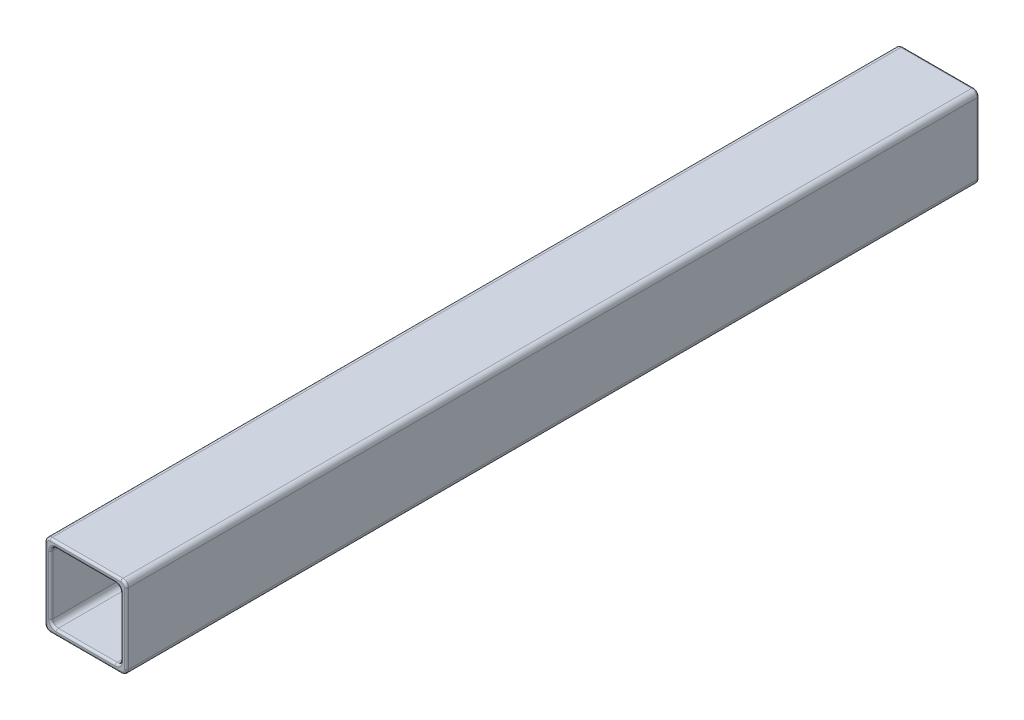
SolidWorks part; units mm, degrees
material "ASTM A500 Grade B Steel"
ref_plane "Front Plane" through (0, 0, 0) normal (0, 0, 1) x (1, 0, 0)
ref_plane "Top Plane" through (0, 0, 0) normal (0, 1, 0) x (1, 0, 0)
ref_plane "Right Plane" through (0, 0, 0) normal (1, 0, 0) x (0, 0, -1)
sketch "Sketch1" plane through (0, 0, 0) normal (0, 0, 1) x (1, 0, 0)
  line L0 (5.3086, -2.7686) -> (32.7914, -2.7686)
  line L1 (2.54, 0) -> (35.56, 0)
  line L2 (0, -2.54) -> (0, -35.56)
  line L3 (2.54, -38.1) -> (35.56, -38.1)
  line L4 (38.1, -2.54) -> (38.1, -35.56)
  line L5 (35.3314, -5.3086) -> (35.3314, -32.7914)
  line L6 (5.3086, -35.3314) -> (32.7914, -35.3314)
  line L7 (2.7686, -5.3086) -> (2.7686, -32.7914)
  line L8 (0, 0) -> (0, -38.1) construction
  line L9 (0, -38.1) -> (38.1, -38.1) construction
  line L10 (38.1, 0) -> (38.1, -38.1) construction
  line L11 (2.7686, -2.7686) -> (2.7686, -35.3314) construction
  line L12 (2.7686, -35.3314) -> (35.3314, -35.3314) construction
  line L13 (35.3314, -2.7686) -> (35.3314, -35.3314) construction
  line L14 (2.7686, -2.7686) -> (35.3314, -2.7686) construction
  line L15 (0, 0) -> (38.1, 0) construction
  arc A0 (0, -35.56) -> (2.54, -38.1) centre (2.54, -35.56) ccw
  arc A1 (38.1, -35.56) -> (35.56, -38.1) centre (35.56, -35.56) cw
  arc A2 (2.7686, -32.7914) -> (5.3086, -35.3314) centre (5.3086, -32.7914) ccw
  arc A3 (32.7914, -35.3314) -> (35.3314, -32.7914) centre (32.7914, -32.7914) ccw
  arc A4 (35.3314, -5.3086) -> (32.7914, -2.7686) centre (32.7914, -5.3086) ccw
  arc A5 (38.1, -2.54) -> (35.56, 0) centre (35.56, -2.54) ccw
  arc A6 (0, -2.54) -> (2.54, 0) centre (2.54, -2.54) cw
  arc A7 (5.3086, -2.7686) -> (2.7686, -5.3086) centre (5.3086, -5.3086) ccw
  point P12 (0, -38.1)
  dimension "D4" = 2.54
  dimension "D3" = 2.7686
extrude "Boss-Extrude1" add sketch "Sketch1" along normal blind 397
sketch "Sketch2" plane through (0, 0, 0) normal (0, 0, -1) x (-1, 0, 0)
  line L0 (-32.7914, -2.7686) -> (-5.3086, -2.7686) construction
  line L1 (-32.7914, -2.7686) -> (-5.3086, -2.7686)
  line L2 (-2.7686, -5.3086) -> (-2.7686, -32.7914) construction
  line L3 (-2.7686, -5.3086) -> (-2.7686, -32.7914)
  line L4 (0, -35.56) -> (0, -2.54)
  line L5 (-2.54, 0) -> (-35.56, 0)
  line L6 (-38.1, -2.54) -> (-38.1, -35.56)
  line L7 (-35.56, -38.1) -> (-2.54, -38.1)
  line L8 (0, -35.56) -> (0, -2.54)
  line L9 (-2.54, 0) -> (-35.56, 0)
  line L10 (-38.1, -2.54) -> (-38.1, -35.56)
  line L11 (-35.56, -38.1) -> (-2.54, -38.1)
  line L12 (-35.3314, -32.7914) -> (-35.3314, -5.3086) construction
  line L13 (-5.3086, -35.3314) -> (-32.7914, -35.3314) construction
  line L14 (-35.3314, -32.7914) -> (-35.3314, -5.3086)
  line L15 (-5.3086, -35.3314) -> (-32.7914, -35.3314)
  arc A0 (-2.7686, -5.3086) -> (-5.3086, -2.7686) centre (-5.3086, -5.3086) ccw construction
  arc A1 (-2.7686, -5.3086) -> (-5.3086, -2.7686) centre (-5.3086, -5.3086) ccw
  arc A2 (-32.7914, -2.7686) -> (-35.3314, -5.3086) centre (-32.7914, -5.3086) ccw construction
  arc A3 (-35.3314, -32.7914) -> (-32.7914, -35.3314) centre (-32.7914, -32.7914) ccw construction
  arc A4 (-2.54, -38.1) -> (0, -35.56) centre (-2.54, -35.56) ccw
  arc A5 (0, -2.54) -> (-2.54, 0) centre (-2.54, -2.54) ccw
  arc A6 (-35.56, 0) -> (-38.1, -2.54) centre (-35.56, -2.54) ccw
  arc A7 (-38.1, -35.56) -> (-35.56, -38.1) centre (-35.56, -35.56) ccw
  arc A8 (-2.54, -38.1) -> (0, -35.56) centre (-2.54, -35.56) ccw
  arc A9 (0, -2.54) -> (-2.54, 0) centre (-2.54, -2.54) ccw
  arc A10 (-35.56, 0) -> (-38.1, -2.54) centre (-35.56, -2.54) ccw
  arc A11 (-38.1, -35.56) -> (-35.56, -38.1) centre (-35.56, -35.56) ccw
  arc A12 (-5.3086, -35.3314) -> (-2.7686, -32.7914) centre (-5.3086, -32.7914) ccw construction
  arc A13 (-32.7914, -2.7686) -> (-35.3314, -5.3086) centre (-32.7914, -5.3086) ccw
  arc A14 (-35.3314, -32.7914) -> (-32.7914, -35.3314) centre (-32.7914, -32.7914) ccw
  arc A15 (-5.3086, -35.3314) -> (-2.7686, -32.7914) centre (-5.3086, -32.7914) ccw
  dimension "D1" = 0
extrude "Boss-Extrude2" add sketch "Sketch2" along normal up to surface (0.6787 mm away)
fillet "Fillet1" radius 1 32 edges at (37.3561, -37.3561, -0.6787) (38.1, -19.05, -0.6787) (37.3561, -0.7439, -0.6787) (19.05, 0, -0.6787) (0.7439, -0.7439, -0.6787) (0, -19.05, -0.6787) (0.7439, -37.3561, -0.6787) (19.05, -38.1, -0.6787) (35.3314, -19.05, -0.6787) (34.5875, -34.5875, -0.6787) (19.05, -35.3314, -0.6787) (3.5125, -34.5875, -0.6787) (2.7686, -19.05, -0.6787) (3.5125, -3.5125, -0.6787) (19.05, -2.7686, -0.6787) (34.5875, -3.5125, -0.6787) (34.5875, -34.5875, 397) (35.3314, -19.05, 397) (34.5875, -3.5125, 397) (19.05, -2.7686, 397) (3.5125, -3.5125, 397) (2.7686, -19.05, 397) (3.5125, -34.5875, 397) (19.05, -35.3314, 397) (0, -19.05, 397) (0.7439, -0.7439, 397) (19.05, 0, 397) (37.3561, -0.7439, 397) (38.1, -19.05, 397) (37.3561, -37.3561, 397) (19.05, -38.1, 397) (0.7439, -37.3561, 397)
